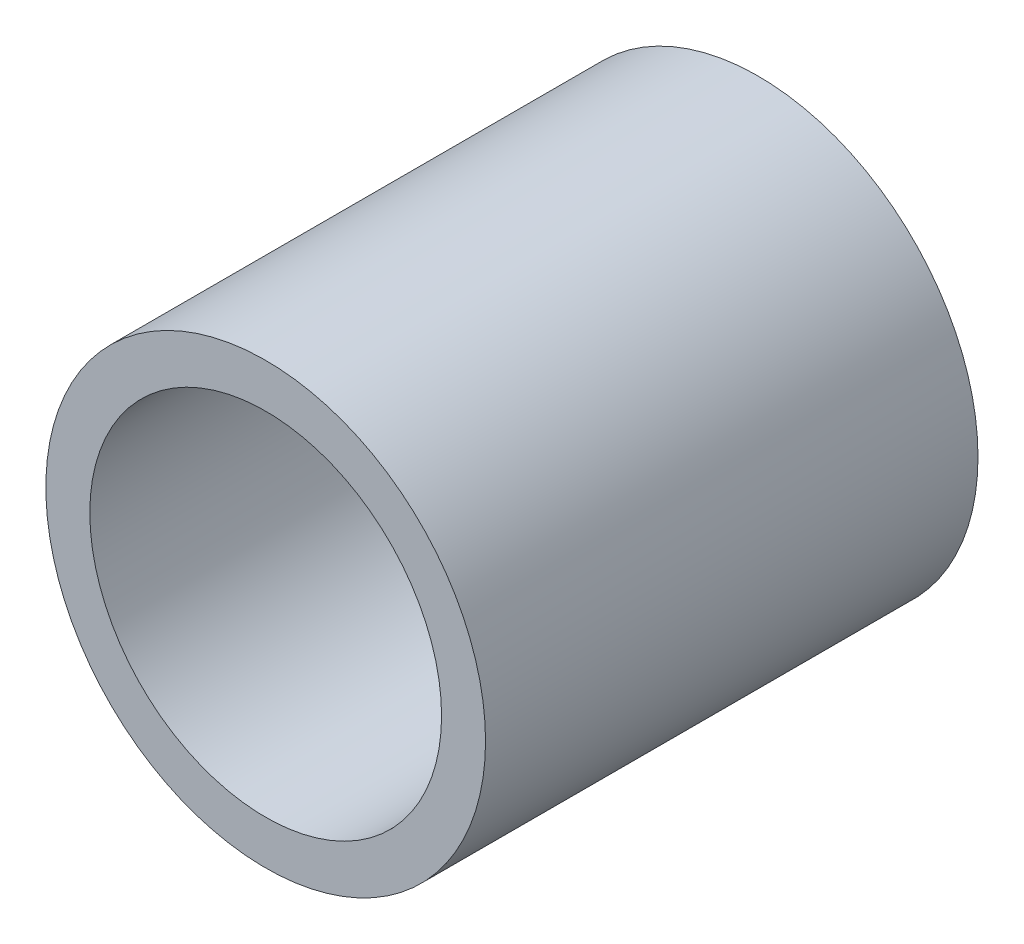
SolidWorks part; units mm, degrees
ref_plane "Спереди" through (0, 0, 0) normal (0, 0, 1) x (1, 0, 0)
ref_plane "Сверху" through (0, 0, 0) normal (0, 1, 0) x (1, 0, 0)
ref_plane "Справа" through (0, 0, 0) normal (1, 0, 0) x (0, 0, -1)
sketch "Sketch1" plane through (0, 0, 0) normal (0, 0, 1) x (1, 0, 0)
  circle A0 centre (0, 0) radius 1
  circle A1 centre (0, 0) radius 1.25
extrude "Extrude1" add sketch "Sketch1" against normal blind 2.8
